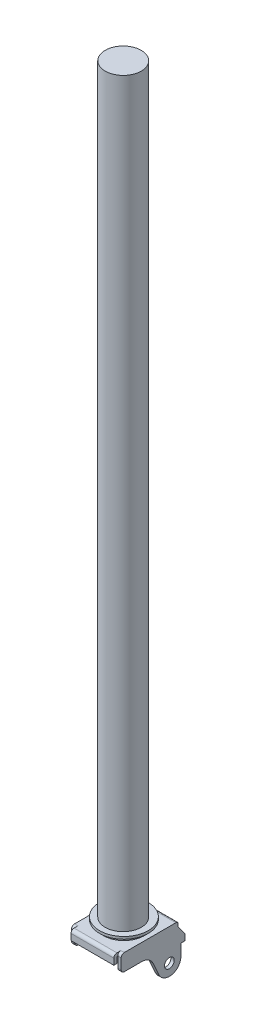
SolidWorks part; units mm, degrees
ref_plane "Front Plane" through (0, 0, 0) normal (0, 0, 1) x (1, 0, 0)
ref_plane "Top Plane" through (0, 0, 0) normal (0, 1, 0) x (1, 0, 0)
ref_plane "Right Plane" through (0, 0, 0) normal (1, 0, 0) x (0, 0, -1)
sketch "Sketch1" plane through (0, 0, 0) normal (0, 1, 0) x (1, 0, 0)
  line L1 (-17.6212, -22.5425) -> (17.6212, -22.5425)
  line L2 (-17.6212, -22.5425) -> (-17.6212, 22.5425)
  line L3 (-17.6212, 22.5425) -> (17.6212, 22.5425)
  line L4 (17.6212, -22.5425) -> (17.6212, 22.5425)
  line L5 (-17.6212, -22.5425) -> (17.6212, 22.5425) construction
  line L6 (-17.6212, 22.5425) -> (17.6212, -22.5425) construction
  point P0 (0, 0)
  dimension "D1" = 35.2425
  dimension "D2" = 45.085
extrude "Boss-Extrude1" add sketch "Sketch1" along normal blind 2.794
sketch "Sketch3" plane through (0, 0, 22.5425) normal (0, 0, 1) x (1, 0, 0)
  line L0 (-17.6212, 2.794) -> (17.6212, 2.794)
  line L1 (-17.6212, 2.794) -> (-17.6212, -4.826)
  line L2 (17.6212, 2.794) -> (17.6212, -4.826)
  line L3 (-17.6212, -4.826) -> (17.6212, -4.826)
  dimension "D1" = 7.62
extrude "Boss-Extrude2" add sketch "Sketch3" along normal blind 2.794
sketch "Sketch4" plane through (0, 0, -22.5425) normal (0, 0, -1) x (-1, 0, 0)
  line L0 (-17.6212, 2.794) -> (17.6212, 2.794)
  line L1 (-17.6212, 2.794) -> (-17.6212, -13.081)
  line L2 (17.6212, 2.794) -> (17.6212, -13.081)
  line L3 (-17.6212, -13.081) -> (17.6212, -13.081)
  dimension "D1" = 15.875
extrude "Boss-Extrude3" add sketch "Sketch4" along normal blind 2.794
sketch "Sketch5" plane through (-17.6212, 0, 0) normal (-1, 0, 0) x (0, 0, 1)
  line L0 (-24.5745, 2.794) -> (-24.5745, -0.2497)
  line L1 (-25.3365, 2.794) -> (25.3365, 2.794) construction
  line L2 (-24.5745, 2.794) -> (19.5707, 2.794)
  line L3 (22.1107, 0.254) -> (22.1107, -8.3566)
  line L4 (-25.3365, -13.081) -> (-25.3365, 2.794) construction
  line L5 (19.5707, -10.8966) -> (5.0683, -10.8966)
  line L6 (-25.0918, -1.786) -> (-30.3911, -8.763)
  line L7 (-30.3911, -8.763) -> (-30.3911, -13.843)
  line L8 (-30.3911, -13.843) -> (-26.9875, -13.843)
  line L9 (-8.8696, -27.2131) -> (-4.1881, -16.8678)
  line L10 (-26.9875, -23.3045) -> (-26.9875, -13.843)
  circle A0 centre (-17.507, -23.3045) radius 3.9942
  arc A1 (-8.8696, -27.2131) -> (-26.9875, -23.3045) centre (-17.507, -23.3045) cw
  arc A2 (22.1107, -8.3566) -> (19.5707, -10.8966) centre (19.5707, -8.3566) cw
  arc A3 (19.5707, 2.794) -> (22.1107, 0.254) centre (19.5707, 0.254) cw
  arc A4 (-24.5745, -0.2497) -> (-25.0918, -1.786) centre (-27.1145, -0.2497) cw
  arc A5 (5.0683, -10.8966) -> (-4.1881, -16.8678) centre (5.0683, -21.0566) ccw
  point P18 (22.1107, -10.8966)
  point P21 (22.1107, 2.794)
  point P24 (-24.5745, -1.1049)
  point P27 (-1.4859, -10.8966)
  dimension "D7" = 7.9883
  dimension "D9" = 5.4864
  dimension "D12" = 2.54
  dimension "D13" = 10.16
  dimension "D1" = 46.6852
  dimension "D2" = 13.6906
  dimension "D3" = 16.637
  dimension "D4" = 3.8989
  dimension "D5" = 5.08
  dimension "D6" = 52.5018
  dimension "D8" = 26.0985
  dimension "D10" = 3.4036
  dimension "D11" = 23.5966
  dimension "D14" = 0.762
extrude "Boss-Extrude5" add sketch "Sketch5" along normal blind 2.794
ref_plane "Plane1" through (0, 0, 0) normal (1, 0, 0) x (0, 0, -1)
mirror "Mirror1" about plane through (0, 0, 0) normal (1, 0, 0) of "Boss-Extrude5"
sketch "Sketch6" plane through (0, 0, 0) normal (1, 0, 0) x (0, 0, -1)
  line L0 (0.5588, 2.794) -> (17.2339, 2.794)
  line L1 (-19.5707, 2.794) -> (24.5745, 2.794) construction
  line L2 (25.3365, 2.794) -> (25.3365, -2.1081) construction
  line L3 (17.2339, 2.794) -> (17.2339, 6.1087)
  line L4 (17.2339, 6.1087) -> (20.5994, 6.1087)
  line L5 (20.5994, 6.1087) -> (20.5994, 8.1153)
  line L6 (0.5588, 2.794) -> (0.5588, 8.1153)
  line L7 (0.5588, 8.1153) -> (20.5994, 8.1153)
  dimension "D1" = 16.6751
  dimension "D2" = 8.1026
  dimension "D3" = 20.0406
  dimension "D4" = 3.3147
  dimension "D5" = 2.0066
revolve "Revolve1" add sketch "Sketch6" angle 360 about L6
sketch "Sketch8" plane through (0, 8.1153, 0) normal (0, 1, 0) x (1, 0, 0)
  circle A0 centre (0, 0) radius 14.8209
  dimension "D1" = 29.6418
extrude "Boss-Extrude6" add sketch "Sketch8" along normal blind 609.6
fillet "Fillet1" radius 2.54 2 edges at (0, 2.794, -25.3365) (0, 2.794, 25.3365)
